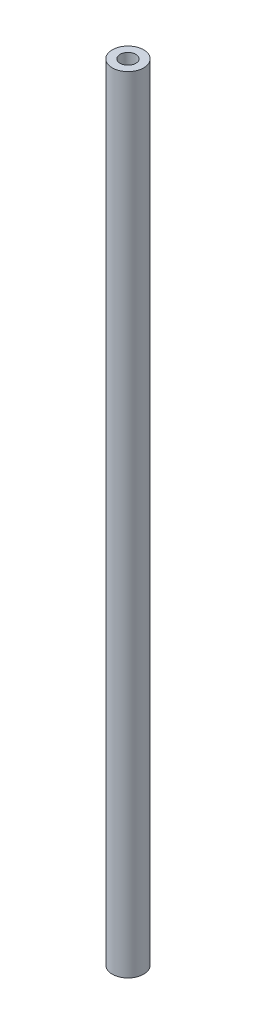
SolidWorks part; units mm, degrees
ref_plane "前视基准面" through (0, 0, 0) normal (0, 0, 1) x (1, 0, 0)
ref_plane "上视基准面" through (0, 0, 0) normal (0, 1, 0) x (1, 0, 0)
ref_plane "右视基准面" through (0, 0, 0) normal (1, 0, 0) x (0, 0, -1)
sketch "草图1" plane through (0, 0, 0) normal (0, 1, 0) x (1, 0, 0)
  circle A0 centre (0, 0) radius 4
  dimension "D1" = 8
extrude "凸台-拉伸1" add sketch "草图1" along normal blind 200
sketch "草图2" plane through (0, 200, 0) normal (0, 1, 0) x (1, 0, 0)
  circle A0 centre (0, 0) radius 2
  dimension "D1" = 4
extrude "切除-拉伸1" cut sketch "草图2" against normal through all
sketch "草图3" plane through (0, 200, 0) normal (0, 1, 0) x (1, 0, 0)
  circle A0 centre (0, 0) radius 4
sketch "草图4" plane through (0, 0, 0) normal (0, -1, 0) x (1, 0, 0)
  circle A0 centre (0, 0) radius 4
